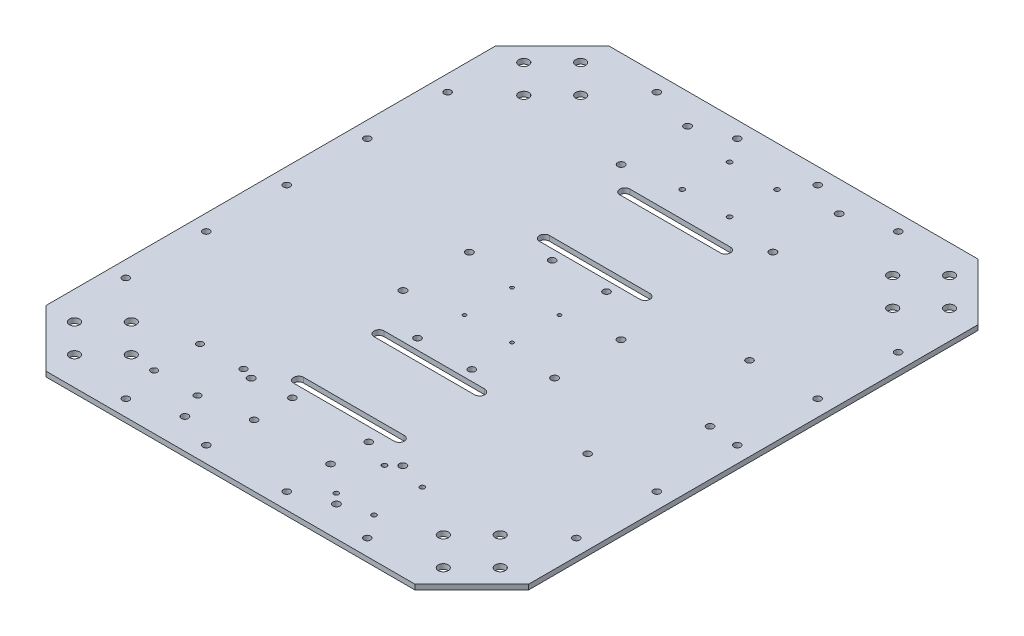
SolidWorks part; units mm, degrees
ref_plane "Front Plane" through (0, 0, 0) normal (0, 0, 1) x (1, 0, 0)
ref_plane "Top Plane" through (0, 0, 0) normal (0, 1, 0) x (1, 0, 0)
ref_plane "Right Plane" through (0, 0, 0) normal (1, 0, 0) x (0, 0, -1)
sketch "Sketch1" plane through (0, 0, 0) normal (0, 1, 0) x (1, 0, 0)
  line L0 (-121.2861, 87.138) -> (-85.365, 123.059)
  line L1 (-121.2861, 123.059) -> (183.5139, 123.059)
  line L2 (-121.2861, 123.059) -> (-121.2861, -232.541)
  line L3 (-121.2861, -232.541) -> (183.5139, -232.541)
  line L4 (183.5139, 123.059) -> (183.5139, -232.541)
  line L5 (31.1139, 95.069) -> (31.1139, -294.9418) construction
  line L6 (-146.0448, -54.741) -> (218.038, -54.741) construction
  line L7 (183.5139, 87.138) -> (147.5929, 123.059)
  line L8 (183.5139, -196.62) -> (147.5929, -232.541)
  line L9 (-121.2861, -196.62) -> (-85.365, -232.541)
  circle A0 centre (-16.7651, 104.009) radius 2.2225
  circle A1 centre (78.9929, 104.009) radius 2.2225
  circle A2 centre (-16.7651, 62.099) radius 2.2225
  circle A3 centre (78.9929, 62.099) radius 2.2225
  circle A4 centre (-16.7651, -171.581) radius 2.2225
  circle A5 centre (78.9929, -171.581) radius 2.2225
  circle A6 centre (78.9929, -213.491) radius 2.2225
  circle A7 centre (-16.7651, -213.491) radius 2.2225
  circle A8 centre (-16.7651, -33.786) radius 2.2225
  circle A9 centre (78.9929, -33.786) radius 2.2225
  circle A10 centre (78.9929, -75.696) radius 2.2225
  circle A11 centre (-16.7651, -75.696) radius 2.2225
  point P8 (31.1139, 123.059)
  point P11 (-121.2861, -54.741)
  dimension "D6" = 95.758
  dimension "D13" = 4.445
  dimension "D1" = 304.8
  dimension "D2" = 355.6
  dimension "D3" = 45
  dimension "D4" = 50.8
  dimension "D5" = 41.91
  dimension "D7" = 104.521
  dimension "D8" = 19.05
  dimension "D9" = 41.91
  dimension "D10" = 20.955
  dimension "D11" = 95.758
  dimension "D12" = 47.879
extrude "Boss-Extrude1" add sketch "Sketch1" along normal blind 3.175
sketch "Sketch2" plane through (0, 3.175, 0) normal (0, 1, 0) x (1, 0, 0)
  line L0 (31.1139, 123.059) -> (31.1139, -287.8465) construction
  line L1 (-85.365, 123.059) -> (147.5929, 123.059) construction
  line L2 (183.5139, -54.741) -> (-158.2106, -54.741) construction
  line L3 (183.5139, 87.138) -> (183.5139, -196.62) construction
  circle A0 centre (13.8419, -12.069) radius 2.159
  circle A1 centre (48.1319, -12.069) radius 2.159
  circle A2 centre (13.8419, -97.159) radius 2.159
  circle A3 centre (48.1319, -97.159) radius 2.159
  dimension "D5" = 4.318
  dimension "D6" = 4.318
  dimension "D7" = 4.318
  dimension "D8" = 4.318
  dimension "D1" = 17.272
  dimension "D2" = 34.29
  dimension "D3" = 85.09
  dimension "D4" = 42.672
extrude "Cut-Extrude1" cut sketch "Sketch2" against normal through all
sketch "Sketch4" plane through (0, 3.175, 0) normal (0, 1, 0) x (1, 0, 0)
  line L0 (-0.6361, 48.256) -> (62.8639, 48.256) construction
  line L1 (-0.6361, 51.431) -> (62.8639, 51.431)
  line L2 (-0.6361, 45.081) -> (62.8639, 45.081)
  line L3 (-0.6361, -2.544) -> (62.8639, -2.544) construction
  line L4 (-0.6361, 0.631) -> (62.8639, 0.631)
  line L5 (-0.6361, -5.719) -> (62.8639, -5.719)
  line L6 (31.1139, 123.059) -> (31.1139, -75.2432) construction
  line L7 (-85.365, 123.059) -> (147.5929, 123.059) construction
  line L8 (-121.2861, -54.741) -> (257.7387, -54.741) construction
  line L9 (-121.2861, 87.138) -> (-121.2861, -196.62) construction
  line L10 (31.1139, -232.541) -> (31.1139, -34.2388) construction
  line L11 (-0.6361, -106.938) -> (62.8639, -106.938) construction
  line L12 (-0.6361, -110.113) -> (62.8639, -110.113)
  line L13 (-0.6361, -103.763) -> (62.8639, -103.763)
  line L14 (-0.6361, -157.738) -> (62.8639, -157.738) construction
  line L15 (-0.6361, -160.913) -> (62.8639, -160.913)
  line L16 (-0.6361, -154.563) -> (62.8639, -154.563)
  arc A0 (-0.6361, 51.431) -> (-0.6361, 45.081) centre (-0.6361, 48.256) ccw
  arc A1 (62.8639, 45.081) -> (62.8639, 51.431) centre (62.8639, 48.256) ccw
  arc A2 (-0.6361, 0.631) -> (-0.6361, -5.719) centre (-0.6361, -2.544) ccw
  arc A3 (62.8639, -5.719) -> (62.8639, 0.631) centre (62.8639, -2.544) ccw
  circle A4 centre (48.1319, -12.069) radius 2.159 construction
  arc A5 (-0.6361, -110.113) -> (-0.6361, -103.763) centre (-0.6361, -106.938) cw
  arc A6 (62.8639, -103.763) -> (62.8639, -110.113) centre (62.8639, -106.938) cw
  arc A7 (-0.6361, -160.913) -> (-0.6361, -154.563) centre (-0.6361, -157.738) cw
  arc A8 (62.8639, -154.563) -> (62.8639, -160.913) centre (62.8639, -157.738) cw
  point P2 (31.1139, 48.256)
  point P7 (31.1139, -2.544)
  point P28 (31.1139, -106.938)
  point P35 (31.1139, -157.738)
  dimension "D1" = 63.5
  dimension "D2" = 63.5
  dimension "D3" = 6.35
  dimension "D4" = 6.35
  dimension "D5" = 44.45
  dimension "D6" = 6.35
extrude "Cut-Extrude2" cut sketch "Sketch4" against normal through all
sketch "Sketch7" plane through (0, 3.175, 0) normal (0, 1, 0) x (1, 0, 0)
  line L0 (31.1139, 123.059) -> (31.1139, -19.2461) construction
  line L3 (-85.365, 123.059) -> (147.5929, 123.059) construction
  circle A0 centre (16.1279, 67.687) radius 1.524
  circle A1 centre (46.0999, 67.687) radius 1.524
  circle A2 centre (16.1279, 97.659) radius 1.524
  circle A3 centre (46.0999, 97.659) radius 1.524
  dimension "D1" = 3.048
  dimension "D2" = 3.048
  dimension "D4" = 14.986
  dimension "D3" = 29.972
  dimension "D5" = 25.4
extrude "Cut-Extrude3" cut sketch "Sketch7" against normal through all
sketch "Sketch8" plane through (0, 3.175, 0) normal (0, 1, 0) x (1, 0, 0)
  line L0 (-85.365, -232.541) -> (147.5929, -232.541) construction
  line L1 (183.5139, 87.138) -> (183.5139, -196.62) construction
  circle A0 centre (73.0239, -207.649) radius 1.524
  circle A1 centre (73.0239, -177.169) radius 1.524
  circle A2 centre (96.8999, -207.649) radius 1.524
  circle A3 centre (96.8999, -177.169) radius 1.524
  dimension "D1" = 3.048
  dimension "D2" = 30.48
  dimension "D3" = 23.876
  dimension "D4" = 24.892
  dimension "D5" = 86.614
extrude "Cut-Extrude4" cut sketch "Sketch8" against normal through all and the other way through all
sketch "Sketch9" plane through (0, 0, 0) normal (0, -1, 0) x (-1, 0, 0)
  line L0 (85.365, -232.541) -> (-147.5929, -232.541) construction
  line L1 (121.2861, 87.138) -> (121.2861, -196.62) construction
  circle A0 centre (51.6494, -197.9691) radius 2.032
  circle A1 centre (24.2174, -197.9691) radius 2.032
  circle A2 centre (51.6494, -169.0131) radius 2.032
  circle A3 centre (24.2174, -169.0131) radius 2.032
  dimension "D1" = 4.064
  dimension "D2" = 27.432
  dimension "D3" = 28.956
  dimension "D4" = 34.5719
  dimension "D5" = 69.6366
extrude "Cut-Extrude5" cut sketch "Sketch9" against normal through all
sketch "Sketch10" plane through (0, 0, 0) normal (0, -1, 0) x (1, 0, 0)
  line L0 (-85.365, 232.541) -> (147.5929, 232.541) construction
  line L1 (31.1139, 232.541) -> (31.1139, 128.7119) construction
  circle A0 centre (6.9839, 193.4758) radius 2.159
  circle A1 centre (55.2439, 193.4758) radius 2.159
  circle A2 centre (6.9839, 169.3458) radius 2.159
  circle A3 centre (55.2439, 169.3458) radius 2.159
  dimension "D1" = 4.318
  dimension "D2" = 48.26
  dimension "D4" = 39.0652
  dimension "D6" = 4.318
  dimension "D7" = 4.318
  dimension "D8" = 4.318
  dimension "D3" = 24.13
  dimension "D5" = 24.13
extrude "Cut-Extrude6" cut sketch "Sketch10" against normal through all
sketch "Sketch13" plane through (0, 0, 0) normal (0, -1, 0) x (1, 0, 0)
  line L0 (31.1139, -123.059) -> (31.1139, 261.4711) construction
  line L1 (-85.365, -123.059) -> (147.5929, -123.059) construction
  line L2 (-121.2861, 54.741) -> (239.2508, 54.741) construction
  line L3 (-121.2861, -87.138) -> (-121.2861, 196.62) construction
  circle A0 centre (16.1139, 69.741) radius 1.1
  circle A1 centre (16.1139, 39.741) radius 1.1
  circle A2 centre (46.1139, 39.741) radius 1.1
  circle A3 centre (46.1139, 69.741) radius 1.1
  dimension "D1" = 2.2
  dimension "D2" = 2.2
  dimension "D3" = 30
  dimension "D4" = 15
  dimension "D5" = 15
extrude "Cut-Extrude8" cut sketch "Sketch13" against normal through all
sketch "Sketch14" plane through (0, 0, 0) normal (0, -1, 0) x (1, 0, 0)
  line L0 (31.1139, 232.541) -> (31.1139, -154.5354) construction
  line L1 (-85.365, 232.541) -> (147.5929, 232.541) construction
  line L2 (-121.2861, 54.741) -> (331.9066, 54.741) construction
  line L3 (-121.2861, -87.138) -> (-121.2861, 196.62) construction
  line L4 (-85.365, 214.5805) -> (-103.3255, 196.62) construction
  line L5 (-103.3255, 196.62) -> (-85.365, 178.6595) construction
  line L6 (-85.365, 178.6595) -> (-67.4045, 196.62) construction
  line L7 (-67.4045, 196.62) -> (-85.365, 214.5805) construction
  line L8 (-121.2861, 196.62) -> (-85.365, 232.541) construction
  line L9 (-103.3255, 214.5805) -> (-48.3665, 159.6215) construction
  circle A0 centre (-103.3255, 196.62) radius 3.175
  circle A1 centre (-85.365, 214.5805) radius 3.175
  circle A2 centre (-85.365, 178.6595) radius 3.175
  circle A3 centre (-67.4045, 196.62) radius 3.175
  circle A4 centre (129.6324, 196.62) radius 3.175
  circle A5 centre (147.5929, 178.6595) radius 3.175
  circle A6 centre (165.5534, 196.62) radius 3.175
  circle A7 centre (147.5929, 214.5805) radius 3.175
  circle A8 centre (-85.365, -105.0985) radius 3.175
  circle A9 centre (-103.3255, -87.138) radius 3.175
  circle A10 centre (-85.365, -69.1774) radius 3.175
  circle A11 centre (-67.4045, -87.138) radius 3.175
  circle A12 centre (165.5534, -87.138) radius 3.175
  circle A13 centre (147.5929, -69.1774) radius 3.175
  circle A14 centre (147.5929, -105.0985) radius 3.175
  circle A15 centre (129.6324, -87.138) radius 3.175
  dimension "D3" = 6.35
  dimension "D4" = 6.35
  dimension "D5" = 6.35
  dimension "D6" = 6.35
  dimension "D2" = 12.7
  dimension "D7" = 90
  dimension "D8" = 25.4
  dimension "D9" = 25.4
  dimension "D10" = 12.7
  dimension "D11" = 90
extrude "Cut-Extrude9" cut sketch "Sketch14" against normal through all
sketch "Sketch15" plane through (0, 0, 0) normal (0, -1, 0) x (1, 0, 0)
  line L0 (31.1139, 232.541) -> (31.1139, 125.875) construction
  line L1 (-85.365, 232.541) -> (147.5929, 232.541) construction
  line L2 (-121.2861, 54.741) -> (75.4631, 54.741) construction
  line L3 (-121.2861, -87.138) -> (-121.2861, 196.62) construction
  circle A0 centre (5.7139, 222.381) radius 2.159
  circle A1 centre (-45.0861, 222.381) radius 2.159
  circle A2 centre (-111.1261, 54.741) radius 2.159
  circle A3 centre (-111.1261, 105.541) radius 2.159
  circle A4 centre (-111.1261, 156.341) radius 2.159
  circle A5 centre (173.3539, 156.341) radius 2.159
  circle A6 centre (173.3539, 105.541) radius 2.159
  circle A7 centre (173.3539, 54.741) radius 2.159
  circle A8 centre (107.3139, 222.381) radius 2.159
  circle A9 centre (56.5139, 222.381) radius 2.159
  circle A10 centre (56.5139, -112.899) radius 2.159
  circle A11 centre (107.3139, -112.899) radius 2.159
  circle A12 centre (173.3539, 3.941) radius 2.159
  circle A13 centre (173.3539, -46.859) radius 2.159
  circle A14 centre (-111.1261, -46.859) radius 2.159
  circle A15 centre (-111.1261, 3.941) radius 2.159
  circle A16 centre (-45.0861, -112.899) radius 2.159
  circle A17 centre (5.7139, -112.899) radius 2.159
  dimension "D3" = 4.318
  dimension "D4" = 4.318
  dimension "D8" = 4.318
  dimension "D9" = 4.318
  dimension "D10" = 4.318
  dimension "D1" = 25.4
  dimension "D2" = 50.8
  dimension "D5" = 10.16
  dimension "D6" = 50.8
  dimension "D7" = 50.8
  dimension "D11" = 10.16
extrude "Cut-Extrude10" cut sketch "Sketch15" against normal through all
sketch "Sketch16" plane through (0, 0, 0) normal (0, -1, 0) x (-1, 0, 0)
  line L1 (-97.5856, -99.6794) -> (-147.4656, -99.6794)
  line L2 (-97.5856, -99.6794) -> (-97.5856, -11.5294)
  line L3 (-97.5856, -11.5294) -> (-147.4656, -11.5294)
  line L4 (-147.4656, -99.6794) -> (-147.4656, -11.5294)
  circle A0 centre (-130.8656, -106.6794) radius 2.159
  circle A1 centre (-130.8656, -4.5294) radius 2.159
  circle A2 centre (-154.4656, -53.0294) radius 2.159
  dimension "D3" = 7
  dimension "D4" = 7
  dimension "D5" = 7
  dimension "D6" = 16.6
  dimension "D7" = 16.6
  dimension "D8" = 46.65
  dimension "D9" = 4.318
  dimension "D10" = 4.318
  dimension "D11" = 4.318
  dimension "D1" = 88.15
  dimension "D2" = 49.88
extrude "Cut-Extrude11" cut sketch "Sketch16" against normal through all contours A2 | A0 | A1
